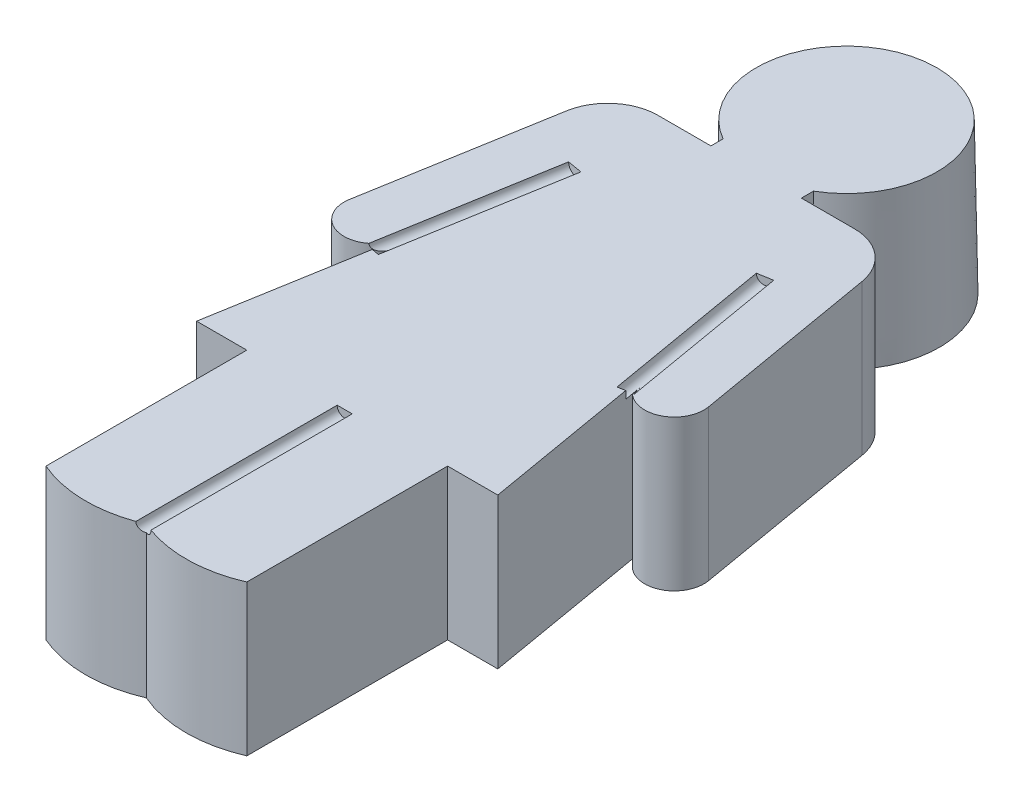
SolidWorks part; units mm, degrees
ref_plane "Alzado" through (0, 0, 0) normal (0, 0, 1) x (1, 0, 0)
ref_plane "Planta" through (0, 0, 0) normal (0, 1, 0) x (1, 0, 0)
ref_plane "Vista lateral" through (0, 0, 0) normal (1, 0, 0) x (0, 0, -1)
sketch "Croquis1" plane through (0, 0, 0) normal (0, 1, 0) x (1, 0, 0)
  line L0 (-10, -35.7305) -> (-10, -15.7305)
  line L3 (10, -35.7305) -> (10, -15.7305)
  line L4 (-9.4373, -35.959) -> (0, -18.5) construction
  line L5 (0, -18.5) -> (9.4373, -35.959) construction
  line L6 (0, -1018.5) -> (0, -37) construction
  line L7 (-9, 25) -> (-14, 25)
  line L8 (-9, 25) -> (9, 25)
  line L9 (-9, 0.0039) -> (-9, 0)
  line L12 (-9, 25) -> (0, 12.5) construction
  line L13 (0, 12.5) -> (9, 25) construction
  line L20 (9, 25) -> (14, 25)
  line L21 (0, -35.7305) -> (0, -18.5) construction
  line L22 (12.0602, 1.3754) -> (15, -15.7305)
  line L23 (-18.918, 12.5) -> (-18.918, -29.2823) construction
  line L24 (0, 12.5) -> (0, 48981.5) construction
  line L25 (-15, -15.7305) -> (-10, -15.7305)
  line L26 (9, 0) -> (10, 0)
  line L27 (-14, 25) -> (-17.888, 2.377)
  line L28 (10, -15.7305) -> (15, -15.7305)
  line L29 (14, 25) -> (17.888, 2.377)
  line L30 (-12.0602, 1.3754) -> (-15, -15.7305)
  arc A0 (-10, -35.7305) -> (0, -35.7305) centre (-5, -24.2205) ccw
  arc A1 (10, -35.7305) -> (0, -35.7305) centre (5, -24.2205) cw
  arc A2 (-17.888, 2.377) -> (-12.0602, 1.3754) centre (-14.9741, 1.8762) ccw
  arc A3 (17.888, 2.377) -> (12.0602, 1.3754) centre (14.9741, 1.8762) cw
  circle A4 centre (0, 34) radius 9
  point P1 (0, -18.5)
  point P13 (0, 12.5)
  point P18 (0, 25)
  dimension "D6" = 30
  dimension "D2" = 20
  dimension "D3" = 25
  dimension "D4" = 18
  dimension "D5" = 5
extrude "Saliente-Extruir1" add sketch "Croquis1" along normal blind 15
sketch "Croquis128" plane through (0, 15, 0) normal (0, 1, 0) x (1, 0, 0)
  line L0 (0, -37.9885) -> (0, -15.9774)
sweep "Cortar-Barrer3" cut path "Croquis128" circular profile diameter 1.5 parameters "D3"=1.5
sketch "Croquis150" plane through (0, 15, 0) normal (0, 1, 0) x (1, 0, 0)
  line L0 (-4.5029, 26.2074) -> (4.5029, 26.2074)
  line L1 (-4.5029, 26.2074) -> (-4.5029, 24.983)
  line L2 (4.5029, 26.2074) -> (4.5029, 24.983)
  line L3 (-4.5029, 24.983) -> (4.5029, 24.983)
  circle A0 centre (0, 34) radius 9 construction
extrude "Saliente-Extruir2" add sketch "Croquis150" against normal blind 15
draft "Ángulo de salida1" type of draft neutral plane draft angle 1 faces to draft 1 face at (0, 7.5, -34.6037) neutral plane through (0, 15, 0) neutral plane normal (0, 1, 0) parameters "D1"=1
fillet "Redondeo1" radius 5 2 edges at (14, 7.5, -25) (-14, 7.5, -25)
sketch "Croquis153" plane through (0, 15, 0) normal (0, 1, 0) x (1, 0, 0)
  line L0 (-12.4344, -0.8019) -> (-9.4762, 16.4106)
  line L1 (0, -1000) -> (0, 49000) construction
  line L2 (12.4344, -0.8019) -> (9.4762, 16.4106)
  line L3 (-12.0602, 1.3754) -> (-15, -15.7305) construction
  point P8 (-12.0602, 1.3754)
  point P9 (0, 0)
  point P10 (-12.2264, 0.4083)
  point P13 (-12.4588, -0.9444)
  point P14 (0, 0)
  point P15 (0, 0)
  point P16 (-12.4344, -0.8019)
sweep "Cortar-Barrer6" cut path "Croquis153" circular profile diameter 1.5 parameters "D3"=1.5
sketch "Croquis222" plane through (0, 15, 0) normal (0, 1, 0) x (1, 0, 0)
  line L0 (-9.4762, 16.4106) -> (11.2744, 16.4106) construction
  line L1 (-8.737, 16.2836) -> (-10.2153, 16.5376) construction
  line L2 (12.0602, 1.3754) -> (9.2328, 17.8266) construction
  line L3 (9.4762, 16.4106) -> (12.3553, -0.3421)
  line L4 (12.0602, 1.3754) -> (15, -15.7305) construction
sweep "Cortar-Barrer7" cut path "Croquis222" circular profile diameter 1.5 parameters "D3"=1.5
